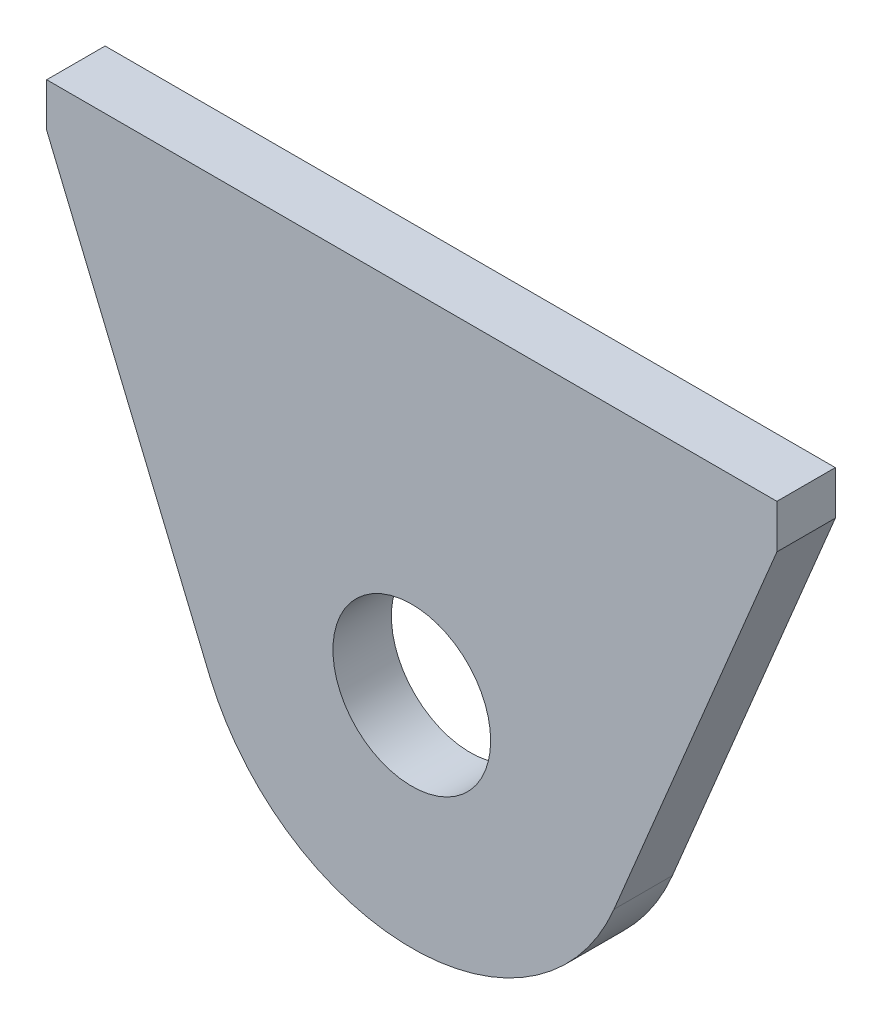
SolidWorks part; units mm, degrees
material "AISI 304"
ref_plane "Спереди" through (0, 0, 0) normal (0, 0, 1) x (1, 0, 0)
ref_plane "Сверху" through (0, 0, 0) normal (0, 1, 0) x (1, 0, 0)
ref_plane "Справа" through (0, 0, 0) normal (1, 0, 0) x (0, 0, -1)
sketch "Эскиз1" plane through (0, 0, 0) normal (0, 0, 1) x (1, 0, 0)
  line L6 (-25, 24) -> (25, 24)
  line L7 (-25, 24) -> (-25, 21)
  line L8 (25, 24) -> (25, 21)
  line L9 (-25, 21) -> (-13.8462, -5.7692)
  line L10 (25, 21) -> (13.8462, -5.7692)
  arc A0 (-13.8462, -5.7692) -> (13.8462, -5.7692) centre (0, 0) ccw
  circle A1 centre (0, 0) radius 5.4
  dimension "D3" = 10.8
  dimension "D4" = 15
  dimension "D1" = 3
  dimension "D2" = 3
  dimension "D5" = 50
  dimension "D6" = 25
  dimension "D7" = 24
extrude "Бобышка-Вытянуть1" add sketch "Эскиз1" along normal blind 4
